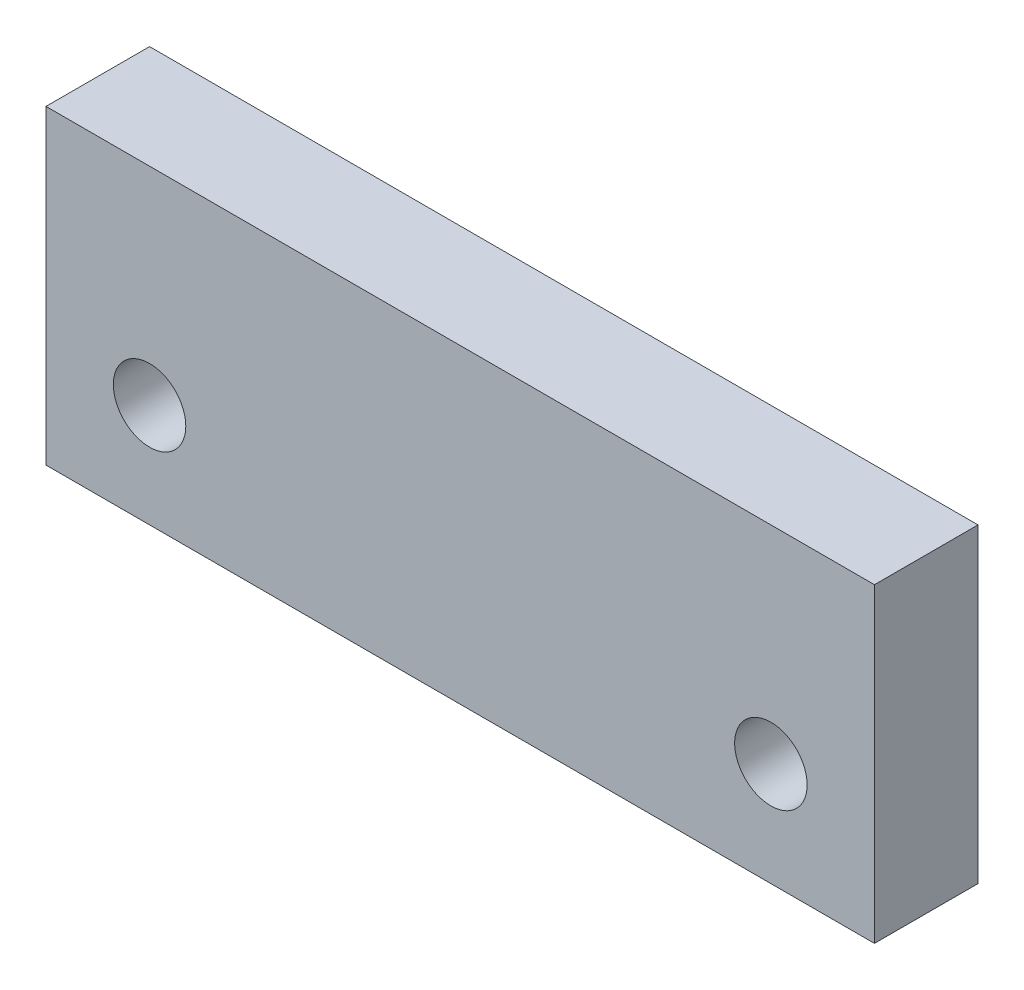
SolidWorks part; units mm, degrees
material "ABS"
ref_plane "Płaszczyzna przednia" through (0, 0, 0) normal (0, 0, 1) x (1, 0, 0)
ref_plane "Płaszczyzna górna" through (0, 0, 0) normal (0, 1, 0) x (1, 0, 0)
ref_plane "Płaszczyzna prawa" through (0, 0, 0) normal (1, 0, 0) x (0, 0, -1)
sketch "Szkic1" plane through (0, 0, 0) normal (0, 0, 1) x (1, 0, 0)
  line L1 (-20, -7.5) -> (20, -7.5)
  line L2 (-20, -7.5) -> (-20, 7.5)
  line L3 (-20, 7.5) -> (20, 7.5)
  line L4 (20, -7.5) -> (20, 7.5)
  line L5 (-20, -7.5) -> (20, 7.5) construction
  line L6 (-20, 7.5) -> (20, -7.5) construction
  circle A0 centre (-15, -2.5) radius 1.75
  circle A1 centre (15, -2.5) radius 1.75
  point P0 (0, 0)
  point P10 (0, 0)
  dimension "D3" = 3.5
  dimension "D1" = 15
  dimension "D2" = 40
  dimension "D4" = 30
  dimension "D5" = 5
  dimension "D6" = 5
extrude "Dodanie-wyciągnięcie1" add sketch "Szkic1" along normal blind 5
